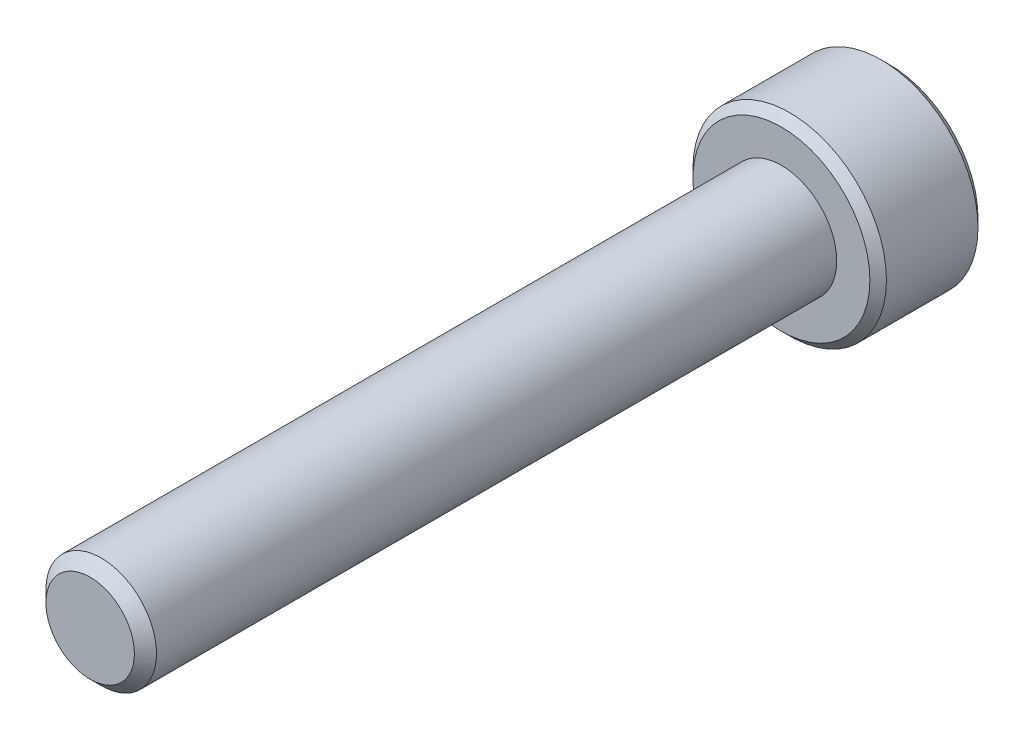
SolidWorks part; units mm, degrees
material "AISI 304"
ref_plane "前视基准面" through (0, 0, 0) normal (0, 0, 1) x (1, 0, 0)
ref_plane "上视基准面" through (0, 0, 0) normal (0, 1, 0) x (1, 0, 0)
ref_plane "右视基准面" through (0, 0, 0) normal (1, 0, 0) x (0, 0, -1)
sketch "草图1" plane through (0, 0, 0) normal (0, 0, 1) x (1, 0, 0)
  circle A0 centre (0, 0) radius 3.5
  dimension "D1" = 7
extrude "凸台-拉伸1" add sketch "草图1" along normal blind 3.91
sketch "草图2" plane through (0, 0, 3.91) normal (0, 0, 1) x (1, 0, 0)
  circle A0 centre (0, 0) radius 2
  dimension "D1" = 4
extrude "凸台-拉伸2" add sketch "草图2" along normal blind 25
sketch "草图3" plane through (0, 0, 0) normal (0, 0, -1) x (-1, 0, 0)
  line L1 (0, 1.7609) -> (-1.525, 0.8805)
  line L2 (-1.525, 0.8805) -> (-1.525, -0.8805)
  line L3 (-1.525, -0.8805) -> (0, -1.7609)
  line L4 (0, -1.7609) -> (1.525, -0.8805)
  line L5 (1.525, -0.8805) -> (1.525, 0.8805)
  line L6 (1.525, 0.8805) -> (0, 1.7609)
  circle A0 centre (0, 0) radius 1.525 construction
  dimension "D1" = 3.05
extrude "切除-拉伸1" cut sketch "草图3" against normal blind 2
chamfer "倒角1" distance 0.4 angle 45 1 edges at (2, 0, 28.91)
chamfer "倒角2" distance 0.3 angle 45 2 edges at (3.5, 0, 3.91) (3.5, 0, 0)
